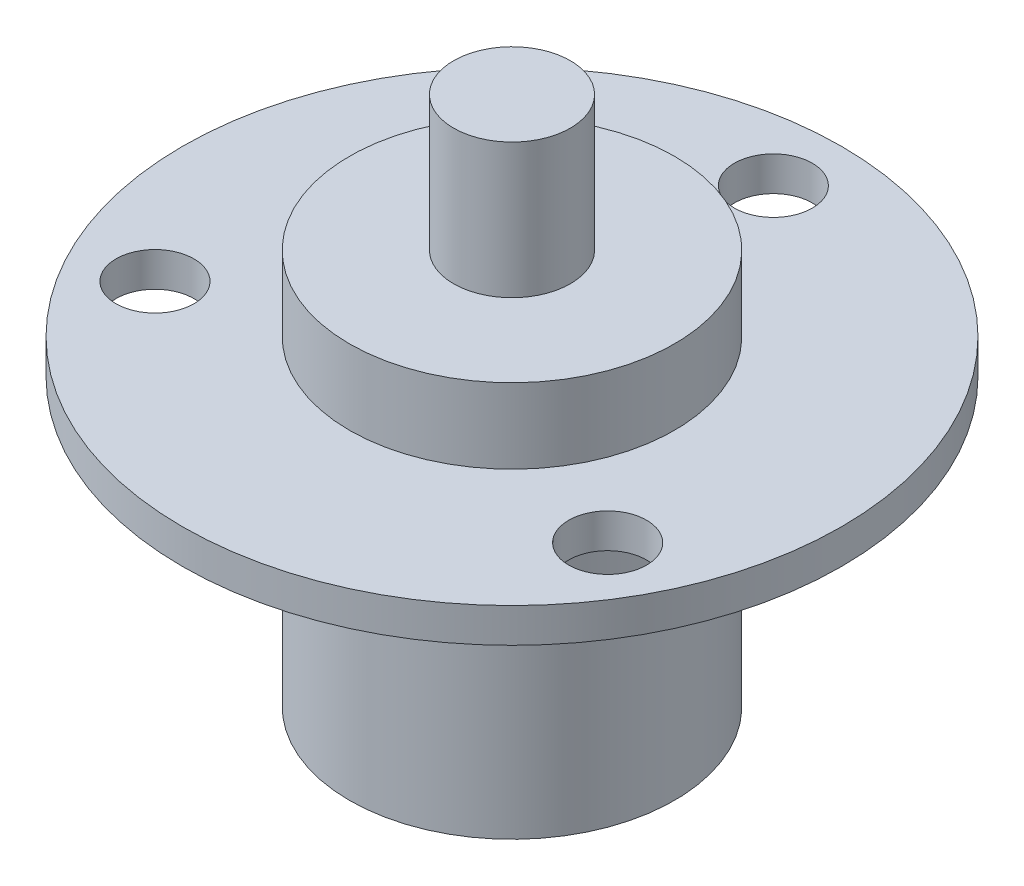
SolidWorks part; units mm, degrees
ref_plane "Front Plane" through (0, 0, 0) normal (0, 0, 1) x (1, 0, 0)
ref_plane "Top Plane" through (0, 0, 0) normal (0, 1, 0) x (1, 0, 0)
ref_plane "Right Plane" through (0, 0, 0) normal (1, 0, 0) x (0, 0, -1)
sketch "Sketch1" plane through (0, 0, 0) normal (0, 1, 0) x (1, 0, 0)
  circle A0 centre (0, 0) radius 22
  dimension "D1" = 44
extrude "Boss-Extrude1" add sketch "Sketch1" along normal blind 2.3
sketch "Sketch2" plane through (0, 2.3, 0) normal (0, 1, 0) x (1, 0, 0)
  circle A0 centre (0, 0) radius 10.85
  dimension "D1" = 21.7
extrude "Boss-Extrude2" add sketch "Sketch2" along normal blind 5 and the other way blind 21.4
sketch "Sketch3" plane through (0, 7.3, 0) normal (0, 1, 0) x (1, 0, 0)
  circle A0 centre (0, 0) radius 3.9
  dimension "D1" = 7.8
extrude "Boss-Extrude3" add sketch "Sketch3" along normal blind 9
sketch "Sketch4" plane through (0, 2.3, 0) normal (0, 1, 0) x (1, 0, 0)
  line L0 (0, 0) -> (0, 17.45) construction
  line L1 (0, 0) -> (-15.1121, -8.725) construction
  line L2 (0, 0) -> (15.1121, -8.725) construction
  circle A0 centre (0, 0) radius 17.45 construction
  circle A1 centre (0, 17.45) radius 2.6
  circle A2 centre (-15.1121, -8.725) radius 2.6
  circle A3 centre (15.1121, -8.725) radius 2.6
  dimension "D1" = 34.9
  dimension "D4" = 5.2
  dimension "D2" = 120
  dimension "D3" = 120
extrude "Cut-Extrude1" cut sketch "Sketch4" against normal through all contours A0 A2 | A0 A3 | A0 A1
